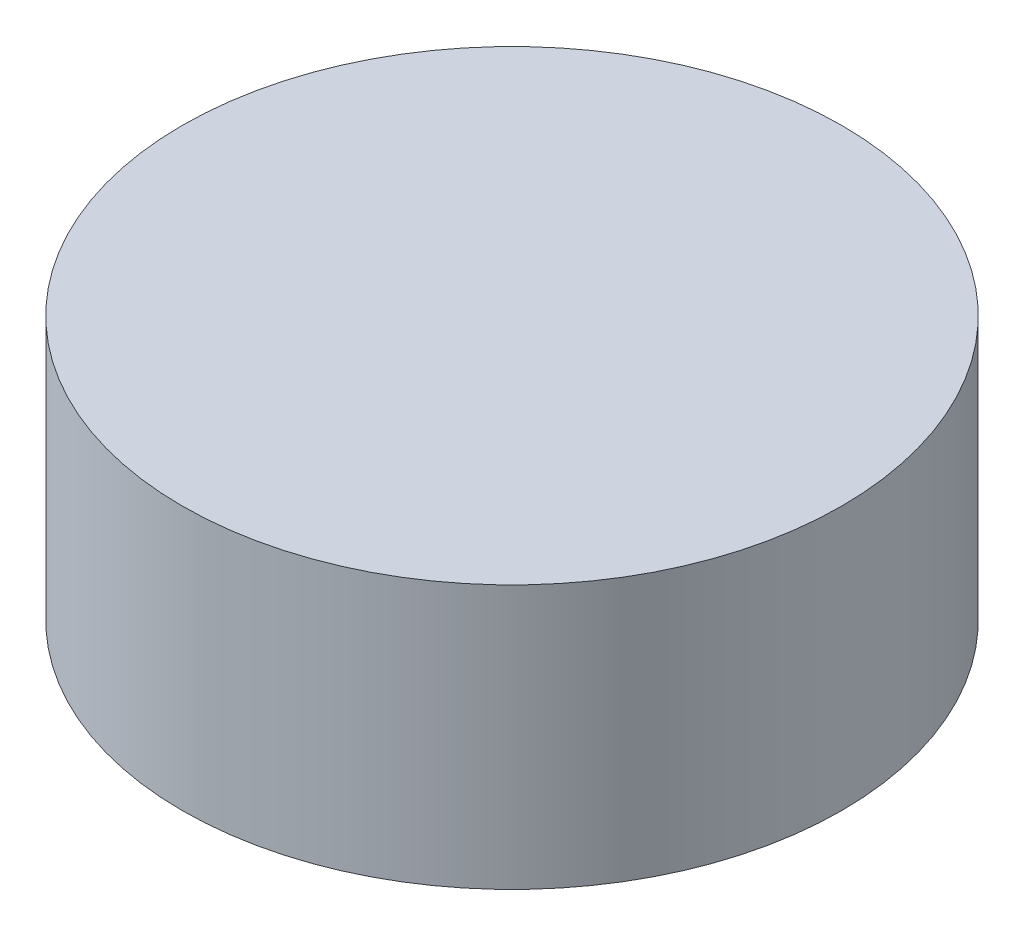
SolidWorks part; units mm, degrees
ref_plane "Front Plane" through (0, 0, 0) normal (0, 0, 1) x (1, 0, 0)
ref_plane "Top Plane" through (0, 0, 0) normal (0, 1, 0) x (1, 0, 0)
ref_plane "Right Plane" through (0, 0, 0) normal (1, 0, 0) x (0, 0, -1)
sketch "Sketch1" plane through (0, 0, 0) normal (0, 1, 0) x (1, 0, 0)
  circle A0 centre (0, 0) radius 31.75
  dimension "D1" = 63.5
extrude "Boss-Extrude1" add sketch "Sketch1" along normal blind 25.4
